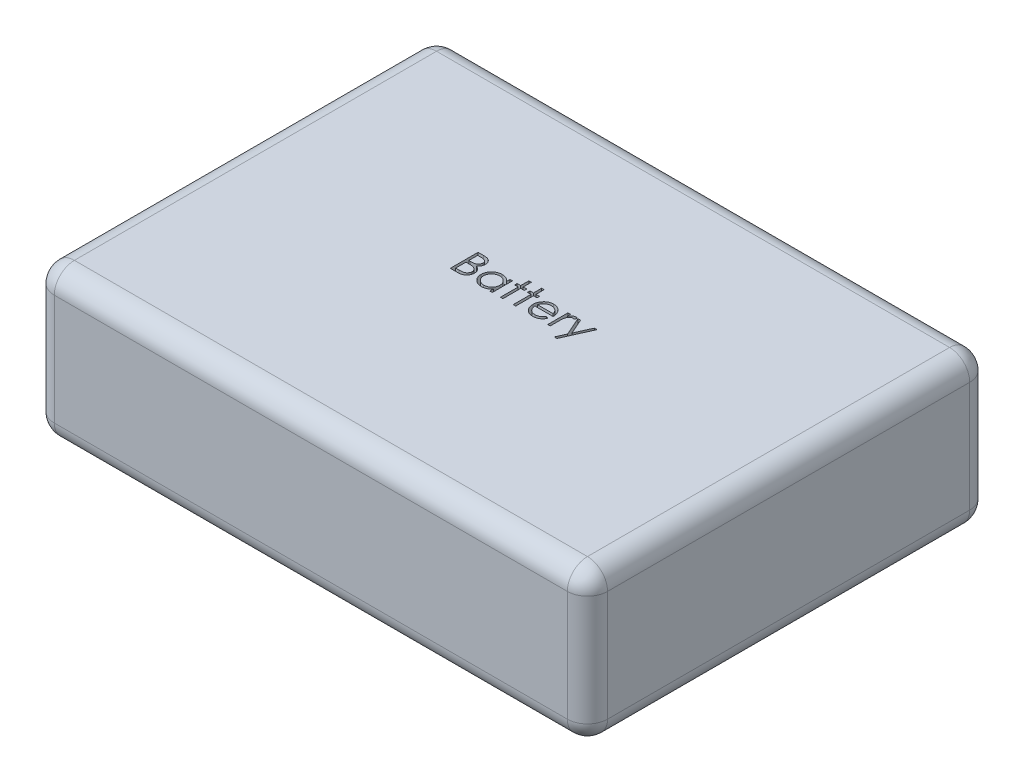
SolidWorks part; units mm, degrees
ref_plane "Front Plane" through (0, 0, 0) normal (0, 0, 1) x (1, 0, 0)
ref_plane "Top Plane" through (0, 0, 0) normal (0, 1, 0) x (1, 0, 0)
ref_plane "Right Plane" through (0, 0, 0) normal (1, 0, 0) x (0, 0, -1)
sketch "Sketch1" plane through (0, 0, 0) normal (0, 1, 0) x (1, 0, 0)
  line L1 (-34.925, 25.4) -> (34.925, 25.4)
  line L2 (-34.925, 25.4) -> (-34.925, -25.4)
  line L3 (-34.925, -25.4) -> (34.925, -25.4)
  line L4 (34.925, 25.4) -> (34.925, -25.4)
  line L5 (-34.925, 25.4) -> (34.925, -25.4) construction
  line L6 (-34.925, -25.4) -> (34.925, 25.4) construction
  point P0 (0, 0)
  dimension "D1" = 69.85
  dimension "D2" = 50.8
extrude "Boss-Extrude1" add sketch "Sketch1" along normal blind 19.05
sketch "Sketch2" plane through (0, 19.05, 0) normal (0, 1, 0) x (1, 0, 0)
  line L1 (-34.925, 0) -> (34.925, 0) construction
  line L2 (-34.925, 25.4) -> (-34.925, -25.4) construction
  line L3 (34.925, -25.4) -> (34.925, 25.4) construction
  text T0 "Battery"
extrude "Cut-Extrude1" cut sketch "Sketch2" against normal blind 2.54
fillet "Fillet1" radius 2.54 12 edges at (0, 0, -25.4) (-34.925, 0, 0) (0, 0, 25.4) (34.925, 0, 0) (0, 19.05, 25.4) (34.925, 19.05, 0) (-34.925, 19.05, 0) (0, 19.05, -25.4) (-34.925, 9.525, -25.4) (-34.925, 9.525, 25.4) (34.925, 9.525, 25.4) (34.925, 9.525, -25.4)
